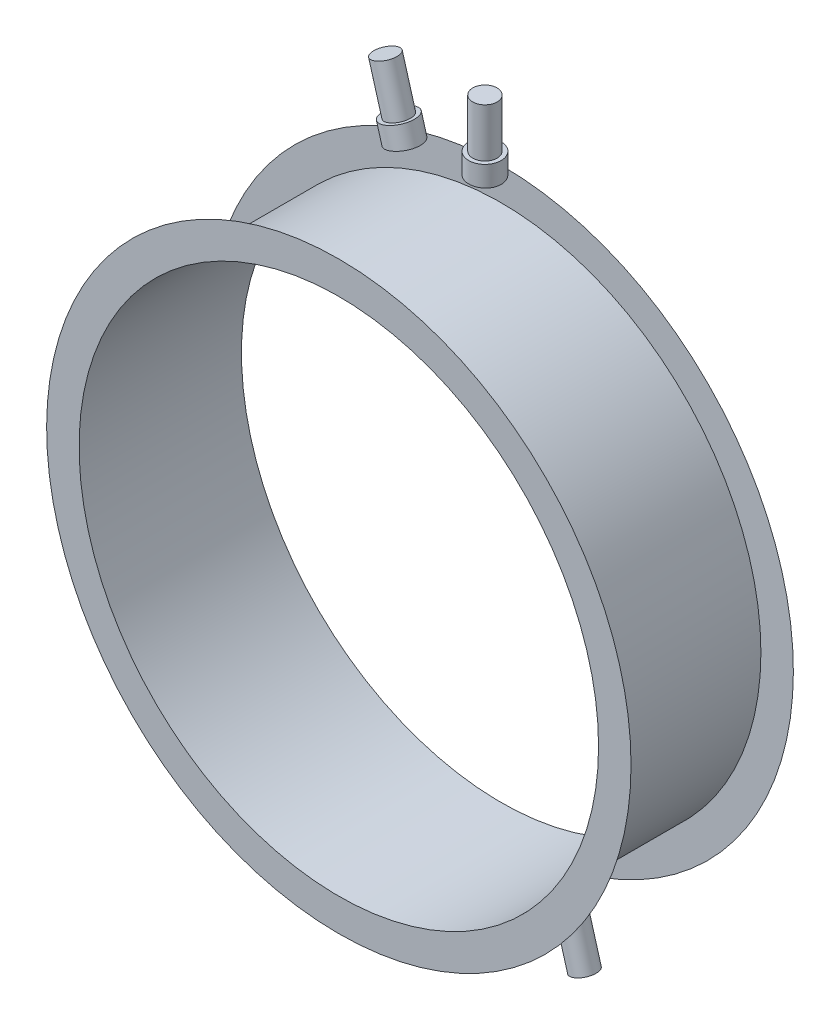
SolidWorks part; units mm, degrees
ref_plane "XY" through (0, 0, 0) normal (0, 0, 1) x (1, 0, 0)
ref_plane "XZ" through (0, 0, 0) normal (0, 1, 0) x (1, 0, 0)
ref_plane "YZ" through (0, 0, 0) normal (1, 0, 0) x (0, 0, -1)
sketch "Sketch1" plane through (0, 0, 0) normal (0, 0, 1) x (1, 0, 0)
  circle A0 centre (0, 0) radius 32
  circle A1 centre (0, 0) radius 36
  dimension "D1" = 64
  dimension "D2" = 72
extrude "Boss-Extrude1" add sketch "Sketch1" along normal mid plane 20
sketch "Sketch5" plane through (0, 0, 0) normal (1, 0, 0) x (0, 0, -1)
  line L0 (6, 32) -> (6, 38.5)
  line L2 (6, 38.5) -> (6.5, 38.5)
  line L3 (6.5, 38.5) -> (6.5, 44.5)
  line L4 (6.5, 44.5) -> (8, 44.5)
  line L5 (8, 44.5) -> (8, 32)
  line L6 (8, 32) -> (6, 32)
  line L7 (10, -32) -> (-10, -32)
  line L8 (-10, 32) -> (10, 32)
  line L9 (-10, 32) -> (10, 32) construction
  line L10 (10, -32) -> (-10, -32) construction
  point P2 (0, 0)
  point P3 (-4.5975, 30.7746)
  point P12 (-3.6248, 32)
  point P13 (0, 0)
  dimension "D1" = 1.5
  dimension "D2" = 2
  dimension "D3" = 2
  dimension "D4" = 38.5
  dimension "D5" = 6
revolve "Revolve1" add sketch "Sketch5" angle 360 about L5
pattern_circular "CirPattern1" count 2 every 16 about axis through (0, 0, 10) along (0, 0, -1) of "Revolve1"
pattern_circular "CirPattern2" count 2 every 180 about axis through (0, 0, 10) along (0, 0, -1) of "CirPattern1", "Revolve1"
